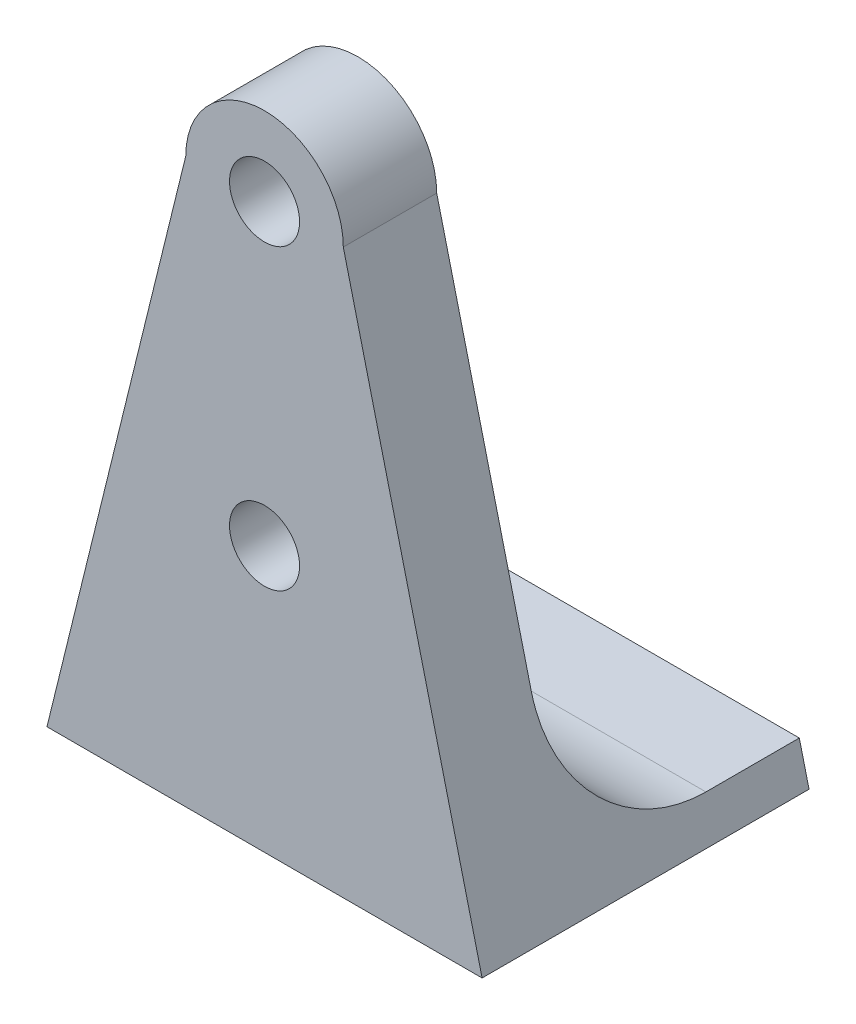
SolidWorks part; units mm, degrees
ref_plane "Front Plane" through (0, 0, 0) normal (0, 0, 1) x (1, 0, 0)
ref_plane "Top Plane" through (0, 0, 0) normal (0, 1, 0) x (1, 0, 0)
ref_plane "Right Plane" through (0, 0, 0) normal (1, 0, 0) x (0, 0, -1)
sketch "Sketch1" plane through (0, 0, 0) normal (0, 0, 1) x (1, 0, 0)
  line L0 (0, 8.506) -> (0, -3.561) construction
  line L1 (-1.6864, 8.506) -> (-4.6585, -3.561)
  line L2 (-4.6585, -3.561) -> (4.6585, -3.561)
  line L3 (0, 8.506) -> (0, 6.439) construction
  line L4 (1.6864, 8.506) -> (4.6585, -3.561)
  arc A0 (1.6864, 8.506) -> (-1.6864, 8.506) centre (0, 8.506) ccw
  dimension "D1" = 10
extrude "Boss-Extrude1" add sketch "Sketch1" along normal blind 2
sketch "Sketch2" plane through (0, 0, 0) normal (0, 0, -1) x (-1, 0, 0)
  line L0 (0, 0) -> (0, -3.561) construction
  line L1 (4.6585, -3.561) -> (-4.6585, -3.561) construction
  line L2 (-4.4501, -2.7149) -> (4.4501, -2.7149)
  line L3 (-4.6585, -3.561) -> (-1.6864, 8.506) construction
  line L4 (-4.4501, -2.7149) -> (-4.6585, -3.561)
  line L5 (-4.6585, -3.561) -> (4.6585, -3.561)
  line L6 (4.4501, -2.7149) -> (4.6585, -3.561)
  point P13 (0, -2.7149)
extrude "Boss-Extrude2" add sketch "Sketch2" along normal blind 5
sketch "Sketch4" plane through (0, 0, 0) normal (1, 0, 0) x (0, 0, -1)
  line L0 (0, 10.1924) -> (5, -2.7149)
  line L1 (5, -2.7149) -> (0, -2.7149) construction
fillet "Fillet1" radius 3 1 edges at (0, -2.7149, 0)
hole_wizard "Ø1.5mm Dowel Hole1" positions "Sketch6" profile "Sketch7" hole size "Ø1.5" standard "ISO" end condition through all
sketch "Sketch6" plane through (0, 0, 2) normal (0, 0, 1) x (1, 0, 0)
  point P0 (0, 8.506)
  point P6 (0, 2.1235)
sketch "Sketch7" plane through (0, 8.506, 2) normal (1, 0, 0) x (0, -1, 0)
  line L0 (0, 0) -> (0, 7)
  line L1 (0, 7) -> (0.75, 7)
  line L2 (0.75, 7) -> (0.75, 0)
  line L5 (0.75, 0) -> (0, 0)
  line L11 (0, -6.35) -> (0, 107.95) construction
  dimension "Thru Hole Dia." = 1.5
  dimension "Thru Hole Depth" = 7
